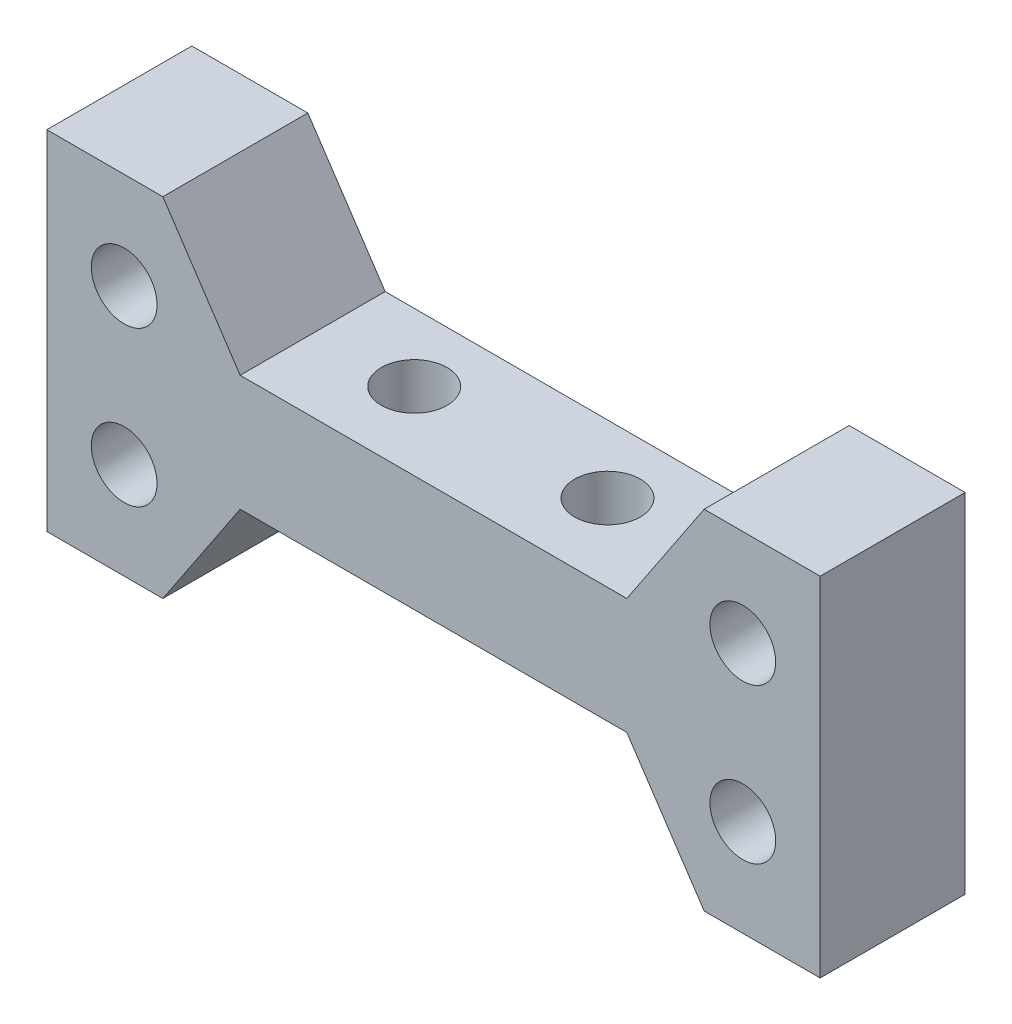
SolidWorks part; units mm, degrees
ref_plane "Front Plane" through (0, 0, 0) normal (0, 0, 1) x (1, 0, 0)
ref_plane "Top Plane" through (0, 0, 0) normal (0, 1, 0) x (1, 0, 0)
ref_plane "Right Plane" through (0, 0, 0) normal (1, 0, 0) x (0, 0, -1)
sketch "Sketch1" plane through (0, 0, 0) normal (0, 0, 1) x (1, 0, 0)
  line L1 (-20, -9) -> (20, -9)
  line L2 (-20, -9) -> (-20, 9)
  line L3 (-20, 9) -> (20, 9)
  line L4 (20, -9) -> (20, 9)
  line L5 (-20, -9) -> (20, 9) construction
  line L6 (-20, 9) -> (20, -9) construction
  point P0 (0, 0)
  dimension "D1" = 40
  dimension "D2" = 18
extrude "Boss-Extrude1" add sketch "Sketch1" along normal blind 7.5
sketch "Sketch2" plane through (0, 0, 0) normal (0, 0, -1) x (-1, 0, 0)
  line L0 (10, -3) -> (14, -9)
  line L1 (20, -9) -> (-20, -9) construction
  line L2 (10, -3) -> (14, -9) construction
  line L3 (14, -9) -> (-14, -9)
  line L4 (-10, -3) -> (-14, -9) construction
  line L5 (-14, -9) -> (-10, -3)
  line L6 (-10, -3) -> (10, -3)
  line L7 (-14, 9) -> (-10, 3)
  line L8 (-20, 9) -> (20, 9) construction
  line L9 (-14, 9) -> (-10, 3) construction
  line L10 (-10, 3) -> (10, 3)
  line L11 (10, 3) -> (14, 9)
  line L12 (14, 9) -> (10, 3) construction
  line L13 (14, 9) -> (-14, 9)
  circle A0 centre (-16, 4) radius 1.7
  circle A1 centre (-16, -4) radius 1.7
  circle A2 centre (16, 4) radius 1.7
  circle A3 centre (16, -4) radius 1.7
extrude "Cut-Extrude1" cut sketch "Sketch2" against normal through all
sketch "Sketch3" plane through (0, 3, 0) normal (0, 1, 0) x (1, 0, 0)
  circle A0 centre (-5, -3.5) radius 1.7
  circle A1 centre (5, -3.5) radius 1.7
extrude "Cut-Extrude2" cut sketch "Sketch3" against normal through all
